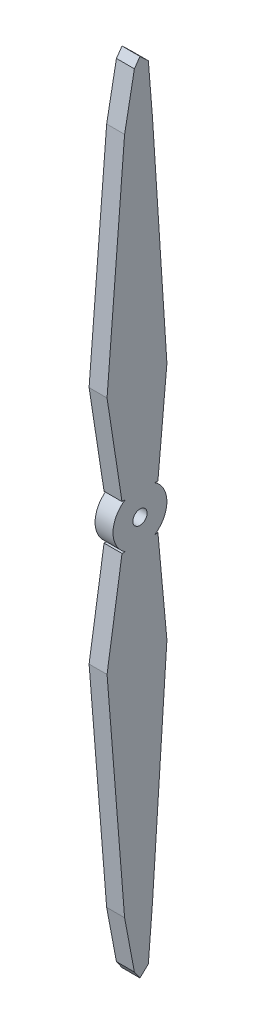
SolidWorks part; units mm, degrees
ref_plane "Front Plane" through (0, 0, 0) normal (0, 0, 1) x (1, 0, 0)
ref_plane "Top Plane" through (0, 0, 0) normal (0, 1, 0) x (1, 0, 0)
ref_plane "Right Plane" through (0, 0, 0) normal (1, 0, 0) x (0, 0, -1)
sketch "Sketch1" plane through (0, 0, 0) normal (1, 0, 0) x (0, 0, -1)
  line L0 (-8.001, 10) -> (-14.6685, 53.34)
  line L1 (-14.6685, 53.34) -> (-6.8453, 151.13)
  line L2 (-6.8453, 151.13) -> (-2.4892, 174.244)
  line L3 (-2.4892, 174.244) -> (0, 177.8)
  line L4 (0, 177.8) -> (3.7338, 174.244)
  line L5 (3.7338, 174.244) -> (5.6007, 151.13)
  line L6 (5.6007, 151.13) -> (12.0015, 53.34)
  line L7 (12.0015, 53.34) -> (8.001, 10)
  line L8 (8.001, 10) -> (-8.001, 10)
  line L9 (-8.001, -10) -> (-14.6685, -53.34)
  line L10 (-14.6685, -53.34) -> (-6.8453, -151.13)
  line L11 (-6.8453, -151.13) -> (-2.4892, -174.244)
  line L12 (-2.4892, -174.244) -> (0, -177.8)
  line L13 (0, -177.8) -> (3.7338, -174.244)
  line L14 (3.7338, -174.244) -> (5.6007, -151.13)
  line L15 (5.6007, -151.13) -> (12.0015, -53.34)
  line L16 (12.0015, -53.34) -> (8.001, -10)
  line L17 (8.001, -10) -> (-8.001, -10)
extrude "Boss-Extrude1" add sketch "Sketch1" against normal blind 8
sketch "Sketch2" plane through (0, 0, 0) normal (1, 0, 0) x (0, 0, -1)
  circle A0 centre (0, 0) radius 12
extrude "Boss-Extrude2" add sketch "Sketch2" against normal blind 8
sketch "Sketch3" plane through (0, 0, 0) normal (1, 0, 0) x (0, 0, -1)
  circle A0 centre (0, 0) radius 3.175
extrude "Cut-Extrude1" cut sketch "Sketch3" against normal through all and the other way through all
